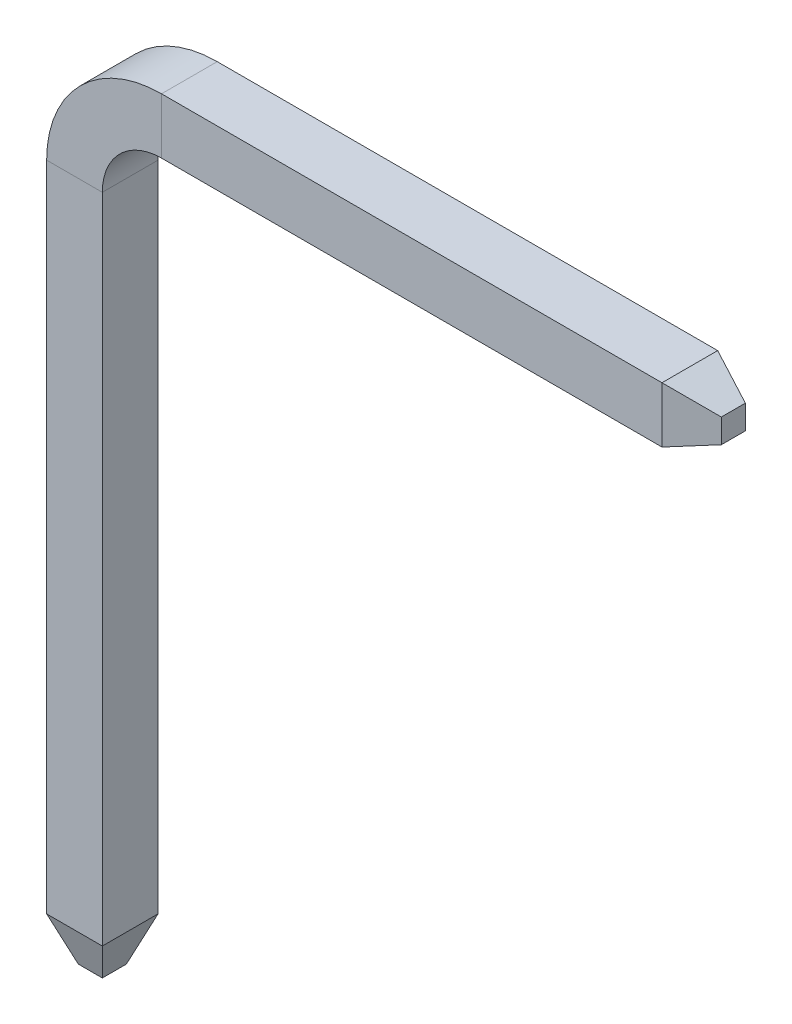
SolidWorks part; units mm, degrees
ref_plane "Спереди" through (0, 0, 0) normal (0, 0, 1) x (1, 0, 0)
ref_plane "Сверху" through (0, 0, 0) normal (0, 1, 0) x (1, 0, 0)
ref_plane "Справа" through (0, 0, 0) normal (1, 0, 0) x (0, 0, -1)
sketch "Эскиз3" plane through (0, 0, 0) normal (0, 1, 0) x (1, 0, 0)
  line L1 (-1.25, 1.25) -> (1.25, 1.25) construction
  line L2 (-1.25, 1.25) -> (-1.25, -1.25) construction
  line L3 (-1.25, -1.25) -> (1.25, -1.25) construction
  line L4 (1.25, 1.25) -> (1.25, -1.25) construction
  line L5 (-1.25, 1.25) -> (1.25, -1.25) construction
  line L6 (-1.25, -1.25) -> (1.25, 1.25) construction
  point P0 (0, 0)
  dimension "D1" = 2.5
sketch "Эскиз4" plane through (0, 0, 0) normal (0, 0, 1) x (1, 0, 0)
  line L0 (-1.25, 1.25) -> (1.25, 1.25) construction
  line L1 (-1.25, 1.25) -> (-1.25, -1.25) construction
  line L2 (-1.25, -1.25) -> (1.25, -1.25) construction
  line L3 (1.25, 1.25) -> (1.25, -1.25) construction
  line L4 (-1.25, 1.25) -> (1.25, -1.25) construction
  line L5 (-1.25, -1.25) -> (1.25, 1.25) construction
  point P0 (0, 0)
  dimension "D1" = 2.5
sketch "Эскиз1" plane through (0, 0, 0) normal (0, 1, 0) x (1, 0, 0)
  line L1 (-0.32, 0.32) -> (0.32, 0.32)
  line L2 (-0.32, 0.32) -> (-0.32, -0.32)
  line L3 (-0.32, -0.32) -> (0.32, -0.32)
  line L4 (0.32, 0.32) -> (0.32, -0.32)
  line L5 (-0.32, 0.32) -> (0.32, -0.32) construction
  line L6 (-0.32, -0.32) -> (0.32, 0.32) construction
  point P0 (0, 0)
  dimension "D1" = 0.64
sketch "Эскиз2" plane through (0, 0, 0) normal (0, 0, 1) x (1, 0, 0)
  line L0 (0, 0) -> (0, 3.75)
  line L1 (1, 4.75) -> (7.25, 4.75)
  line L3 (0, 0) -> (0, -4.25)
  line L4 (1.25, 1.25) -> (1.25, -1.25) construction
  line L6 (-1.25, -1.25) -> (1.25, -1.25) construction
  arc A0 (0, 3.75) -> (1, 4.75) centre (1, 3.75) cw
  dimension "D4" = 1
  dimension "D1" = 6
  dimension "D2" = 6
  dimension "D3" = 3
sweep "По траектории1" add profiles "Эскиз1" path "Эскиз2"
chamfer "Фаска1" distance 0.5 angle 20 4 edges at (7.25, 4.75, 0.32) (7.25, 5.07, 0) (7.25, 4.75, -0.32) (7.25, 4.43, 0)
chamfer "Фаска2" distance 0.5 angle 20 4 edges at (0, -4.25, -0.32) (-0.32, -4.25, 0) (0, -4.25, 0.32) (0.32, -4.25, 0)
sketch "Эскиз5" plane through (0, 0, 0) normal (0, 0, 1) x (1, 0, 0)
  line L0 (0, -8.1573) -> (0, 6.6577) construction
  line L2 (-2.4103, 4.75) -> (5.9307, 4.75) construction
  line L3 (7.25, 4.888) -> (7.25, 4.612) construction
  point P7 (7.25, 4.75)
